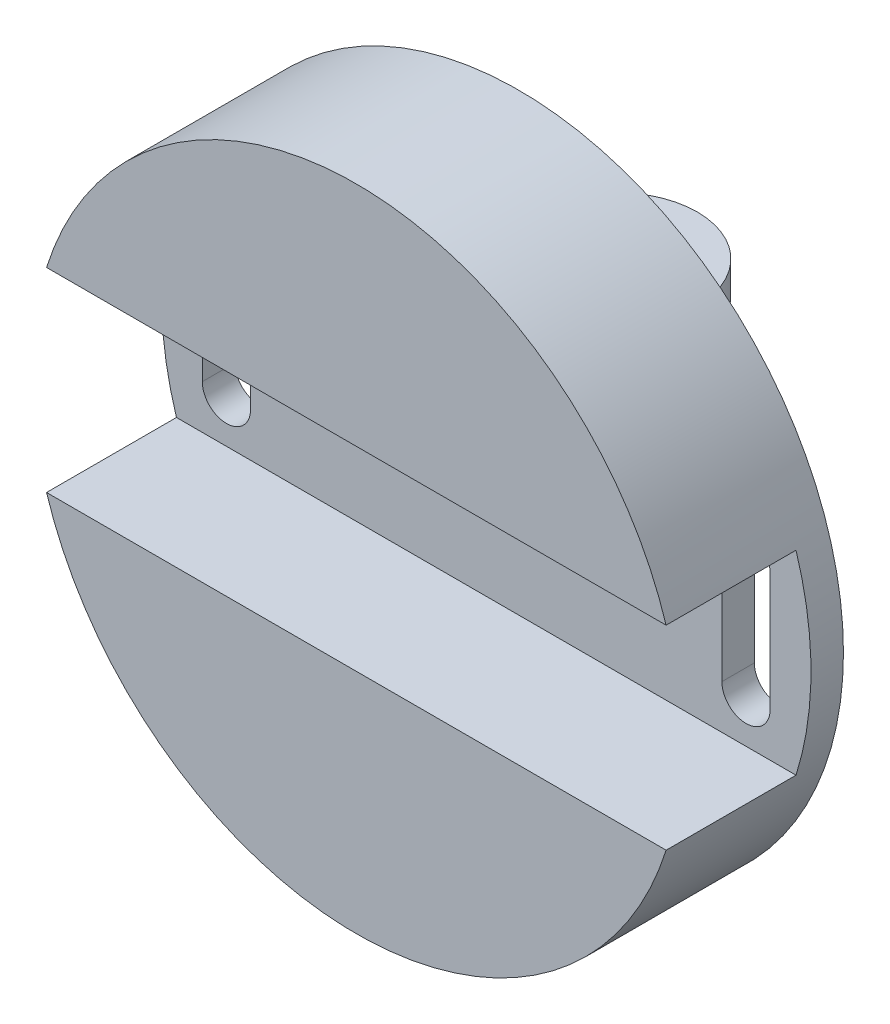
SolidWorks part; units mm, degrees
ref_plane "前基準面" through (0, 0, 0) normal (0, 0, 1) x (1, 0, 0)
ref_plane "上基準面" through (0, 0, 0) normal (0, 1, 0) x (1, 0, 0)
ref_plane "右基準面" through (0, 0, 0) normal (1, 0, 0) x (0, 0, -1)
sketch "草圖1" plane through (0, 0, 0) normal (0, 0, 1) x (1, 0, 0)
  circle A0 centre (0, 0) radius 50
  dimension "D1" = 100
extrude "填料-伸長1" add sketch "草圖1" along normal blind 25
sketch "草圖3" plane through (0, 0, 0) normal (0, 0, -1) x (-1, 0, 0)
  line L0 (-64.0801, 0) -> (79.9224, 0) construction
  line L1 (-25, 40) -> (25, 40)
  line L2 (-25, 40) -> (-25, 20)
  line L3 (-25, 20) -> (25, 20)
  line L4 (25, 40) -> (25, 20)
  line L5 (-25, -40) -> (25, -40)
  line L6 (25, -40) -> (25, -20)
  line L7 (-25, -40) -> (-25, -20)
  line L8 (-25, -20) -> (25, -20)
  dimension "D1" = 20
  dimension "D2" = 50
  dimension "D3" = 25
  dimension "D4" = 20
extrude "除料-伸長1" cut sketch "草圖3" against normal blind 20
sketch "草圖6" plane through (0, 0, 0) normal (0, 0, -1) x (-1, 0, 0)
  line L0 (-25, 20) -> (25, 20) construction
  line L1 (-12.5, 20) -> (12.5, 20)
  line L2 (-12.5, 20) -> (-12.5, 15)
  line L3 (-12.5, 15) -> (12.5, 15)
  line L4 (12.5, 20) -> (12.5, 15)
  line L5 (-58.8746, 0) -> (103.0107, 0) construction
  line L6 (-12.5, -20) -> (-12.5, -15)
  line L7 (12.5, -20) -> (12.5, -15)
  line L8 (-12.5, -20) -> (12.5, -20)
  line L9 (-12.5, -15) -> (12.5, -15)
  dimension "D1" = 25
  dimension "D2" = 5
  dimension "D3" = 12.5
extrude "填料-伸長2" add sketch "草圖6" along normal blind 15
sketch "草圖7" plane through (0, 20, 0) normal (0, 1, 0) x (1, 0, 0)
  line L0 (50, 0) -> (-50, 0) construction
  circle A0 centre (0, 12.5) radius 2.5
  dimension "D1" = 5
  dimension "D2" = 12.5
sketch "草圖8" plane through (0, -20, 0) normal (0, -1, 0) x (1, 0, 0)
  line L0 (12.5, -15) -> (-12.5, -15) construction
  line L1 (12.5, -15) -> (12.5, 0) construction
  line L2 (-12.5, -15) -> (12.5, -15)
  arc A0 (-12.5, -15) -> (12.5, -15) centre (0, -15) ccw
extrude "填料-伸長3" add sketch "草圖8" against normal blind 5
mirror "鏡射1" about plane through (0, 0, 0) normal (0, 1, 0) of "填料-伸長3"
extrude "除料-伸長2" cut sketch "草圖7" against normal through all
sketch "草圖9" plane through (0, 0, 25) normal (0, 0, 1) x (1, 0, 0)
  line L1 (-69.1119, 15) -> (68.448, 15)
  line L2 (-69.1119, 15) -> (-69.1119, -15)
  line L3 (-69.1119, -15) -> (68.448, -15)
  line L4 (68.448, 15) -> (68.448, -15)
  dimension "D1" = 30
  dimension "D2" = 15
extrude "除料-伸長3" cut sketch "草圖9" against normal blind 20
sketch "草圖10" plane through (0, 0, 5) normal (0, 0, 1) x (1, 0, 0)
  line L0 (-40, 9.9585) -> (-40, -8.2324) construction
  line L1 (-36.2822, 9.9585) -> (-36.2822, -8.2324)
  line L2 (-43.7178, 9.9585) -> (-43.7178, -8.2324)
  line L3 (0, 53.112) -> (0, -55.502) construction
  line L4 (40, 9.9585) -> (40, -8.2324) construction
  line L5 (36.2822, 9.9585) -> (36.2822, -8.2324)
  line L6 (43.7178, 9.9585) -> (43.7178, -8.2324)
  arc A0 (-36.2822, 9.9585) -> (-43.7178, 9.9585) centre (-40, 9.9585) ccw
  arc A1 (-43.7178, -8.2324) -> (-36.2822, -8.2324) centre (-40, -8.2324) ccw
  arc A2 (36.2822, 9.9585) -> (43.7178, 9.9585) centre (40, 9.9585) cw
  arc A3 (43.7178, -8.2324) -> (36.2822, -8.2324) centre (40, -8.2324) cw
  point P2 (-40, 0.8631)
  point P12 (40, 0.8631)
  dimension "D1" = 40
extrude "除料-伸長4" cut sketch "草圖10" against normal through all
